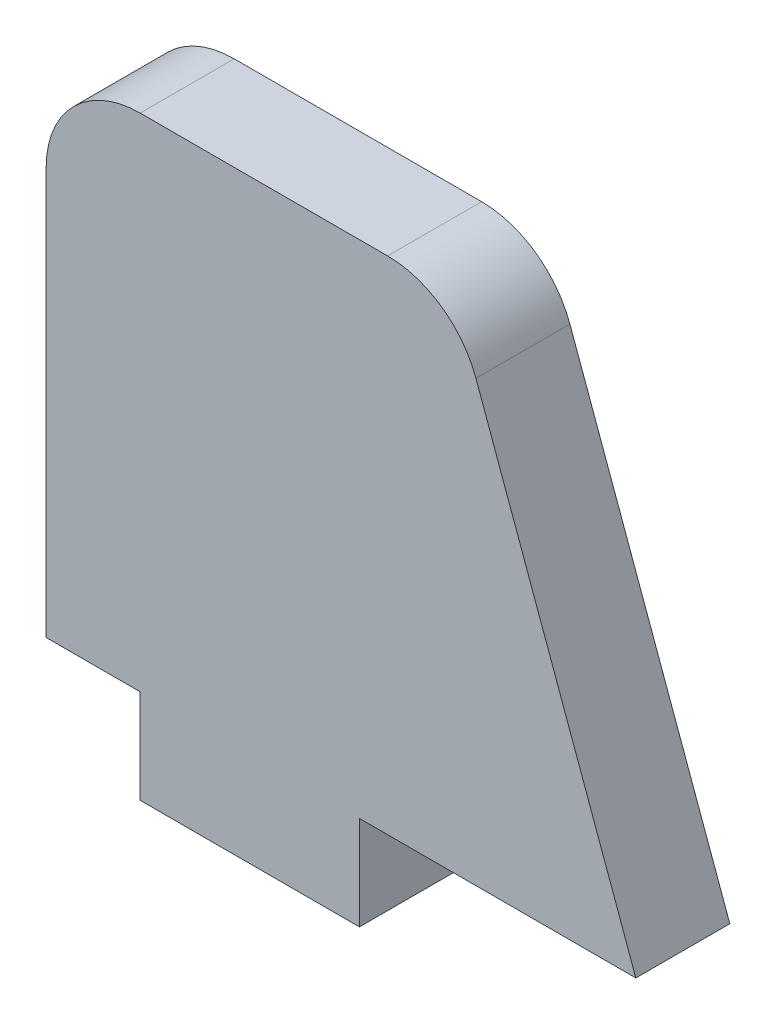
SolidWorks part; units mm, degrees
material "Acrylic (Medium-high impact)"
ref_plane "Front Plane" through (0, 0, 0) normal (0, 0, 1) x (1, 0, 0)
ref_plane "Top Plane" through (0, 0, 0) normal (0, 1, 0) x (1, 0, 0)
ref_plane "Right Plane" through (0, 0, 0) normal (1, 0, 0) x (0, 0, -1)
sketch "Esboço1" plane through (0, 0, 0) normal (0, 0, 1) x (1, 0, 0)
  line L0 (-6.5, -8) -> (-6.5, 8)
  line L1 (-6.5, 8) -> (6.5, 8)
  line L2 (6.5, 8) -> (12.3235, -8)
  line L3 (12.3235, -8) -> (3.5, -8)
  line L4 (-3.5, -8) -> (-3.5, -11)
  line L5 (-3.5, -11) -> (3.5, -11)
  line L6 (3.5, -11) -> (3.5, -8)
  line L7 (-3.5, -8) -> (-6.5, -8)
  point P5 (0, 8)
  point P10 (-3, -1.6256)
  point P11 (-1.9681, -1.6256)
  point P12 (-4.7476, -4.6368)
  point P13 (7.5, 4.3967)
  point P14 (11.2057, -2.0599)
  point P15 (-6.5, 0)
  point P16 (7.5, 9)
  point P17 (16.2994, -9)
  point P18 (-4.616, -9)
  point P19 (0, -11)
  point P20 (17.2118, -9)
  dimension "D1" = 3
  dimension "D3" = 7
  dimension "D4" = 16
  dimension "D5" = 70
  dimension "D6" = 3
extrude "Ressalto-extrusão1" add sketch "Esboço1" along normal mid plane 3
fillet "Filete1" radius 3 2 edges at (6.5, 8, 0) (-6.5, 8, 0)
